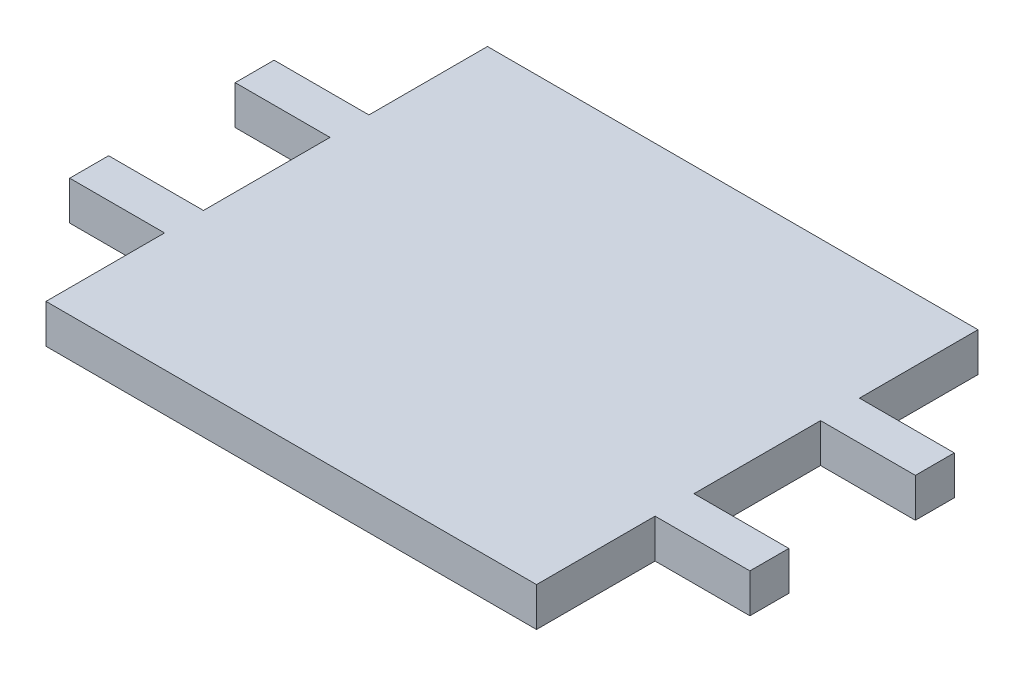
SolidWorks part; units mm, degrees
ref_plane "Front Plane" through (0, 0, 0) normal (0, 0, 1) x (1, 0, 0)
ref_plane "Top Plane" through (0, 0, 0) normal (0, 1, 0) x (1, 0, 0)
ref_plane "Right Plane" through (0, 0, 0) normal (1, 0, 0) x (0, 0, -1)
sketch "Sketch1" plane through (0, 0, 0) normal (0, 1, 0) x (1, 0, 0)
  line L0 (0, 34.29) -> (0, -34.29) construction
  line L1 (-38.1, 34.29) -> (38.1, 34.29)
  line L2 (-38.1, 34.29) -> (-38.1, -34.29)
  line L3 (-38.1, -34.29) -> (38.1, -34.29)
  line L4 (38.1, 34.29) -> (38.1, -34.29)
  line L5 (-38.1, 0) -> (38.1, 0) construction
  line L6 (-52.832, 9.8298) -> (-52.832, -9.8298) construction
  line L7 (-52.832, 15.875) -> (-38.1, 15.875)
  line L8 (-52.832, 15.875) -> (-52.832, 9.8298)
  line L9 (-52.832, 9.8298) -> (-38.1, 9.8298)
  line L10 (-38.1, 15.875) -> (-38.1, 9.8298)
  line L11 (-52.832, -9.8298) -> (-38.1, -9.8298)
  line L12 (-52.832, -9.8298) -> (-52.832, -15.875)
  line L13 (-52.832, -15.875) -> (-38.1, -15.875)
  line L14 (-38.1, -9.8298) -> (-38.1, -15.875)
  line L15 (52.832, -15.875) -> (38.1, -15.875)
  line L16 (38.1, -9.8298) -> (38.1, -15.875)
  line L17 (52.832, -9.8298) -> (38.1, -9.8298)
  line L18 (52.832, -9.8298) -> (52.832, -15.875)
  line L19 (52.832, 9.8298) -> (38.1, 9.8298)
  line L20 (38.1, 15.875) -> (38.1, 9.8298)
  line L21 (52.832, 15.875) -> (38.1, 15.875)
  line L22 (52.832, 15.875) -> (52.832, 9.8298)
  point P4 (0, 34.29)
  point P6 (-38.1, 0)
  point P19 (-52.832, 0)
  dimension "D1" = 76.2
  dimension "D2" = 68.58
  dimension "D3" = 14.732
  dimension "D4" = 6.0452
  dimension "D5" = 14.732
  dimension "D6" = 6.0452
  dimension "D7" = 31.75
extrude "Boss-Extrude1" add sketch "Sketch1" along normal blind 6.0452 contours L4 L1 L2 L3 | L12 L13 L2 L11 | L8 L9 L2 L7 | L22 L21 L4 L19 | L18 L17 L4 L15
